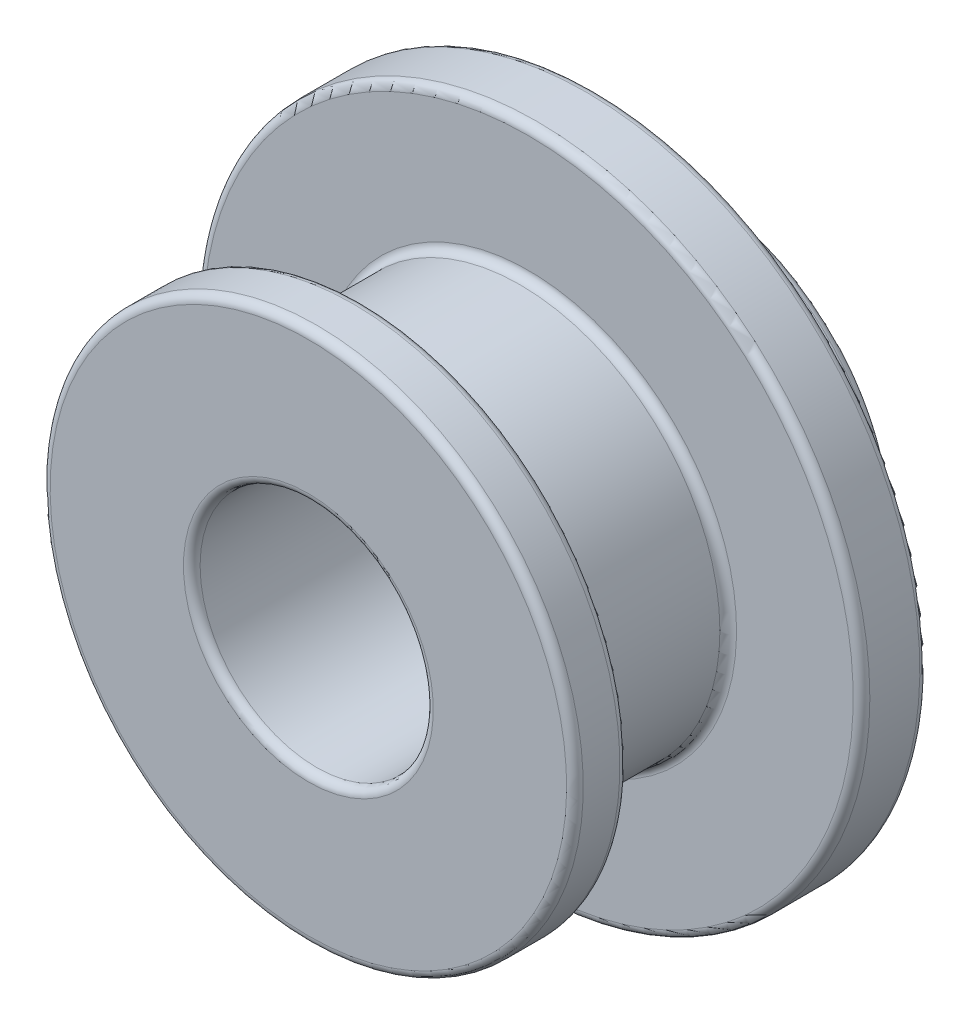
SolidWorks part; units mm, degrees
material "Plain Carbon Steel"
ref_plane "Front Plane" through (0, 0, 0) normal (0, 0, 1) x (1, 0, 0)
ref_plane "Top Plane" through (0, 0, 0) normal (0, 1, 0) x (1, 0, 0)
ref_plane "Right Plane" through (0, 0, 0) normal (1, 0, 0) x (0, 0, -1)
sketch "Sketch1" plane through (0, 0, 0) normal (1, 0, 0) x (0, 0, -1)
  line L0 (0, 8) -> (0, 6)
  line L1 (0, 6) -> (5, 6)
  line L2 (5, 6) -> (5, 10)
  line L3 (5, 10) -> (7, 10)
  line L4 (7, 10) -> (7, 6)
  line L5 (7, 6) -> (10, 6)
  line L6 (10, 6) -> (10, 0)
  line L7 (10, 0) -> (5, 0)
  line L8 (5, 0) -> (5, 3.5)
  line L9 (5, 3.5) -> (-1.6, 3.5)
  line L10 (-1.6, 3.5) -> (-1.6, 8)
  line L11 (-1.6, 8) -> (0, 8)
  dimension "D1" = 3.5
  dimension "D2" = 6
  dimension "D3" = 8
  dimension "D4" = 1.6
  dimension "D5" = 10
  dimension "D6" = 2
  dimension "D7" = 5
  dimension "D8" = 10
revolve "Revolve1" add sketch "Sketch1" angle 360 about L7
hole_wizard "M6x1.0 Tapped Hole1" positions "Sketch2" profile "Sketch3" tap size "M6x1.0" standard "ANSI Metric" end condition up to next
sketch "Sketch2" plane through (0, 0, -5) normal (0, 0, 1) x (1, 0, 0)
  point P0 (0, 0)
sketch "Sketch3" plane through (0, 0, -5) normal (1, 0, 0) x (0, -1, 0)
  line L0 (0, 0) -> (0, 5)
  line L1 (0, 5) -> (2.5, 5)
  line L2 (2.5, 5) -> (2.5, 0)
  line L5 (2.5, 0) -> (0, 0)
  line L11 (0, -6.35) -> (0, 107.95) construction
  dimension "Thru Tap Drill Dia." = 5
  dimension "Thru Tap Drill Depth" = 5
cosmetic thread "Hole Thread1" parameters "D2"=6
fillet "Fillet1" radius 0.25 9 edges at (0, 6, -10) (0, 6, -7) (0, 10, -7) (0, 10, -5) (0, 6, -5) (0, 6, 0) (0, 8, 0) (0, 8, 1.6) (0, 3.5, 1.6)
